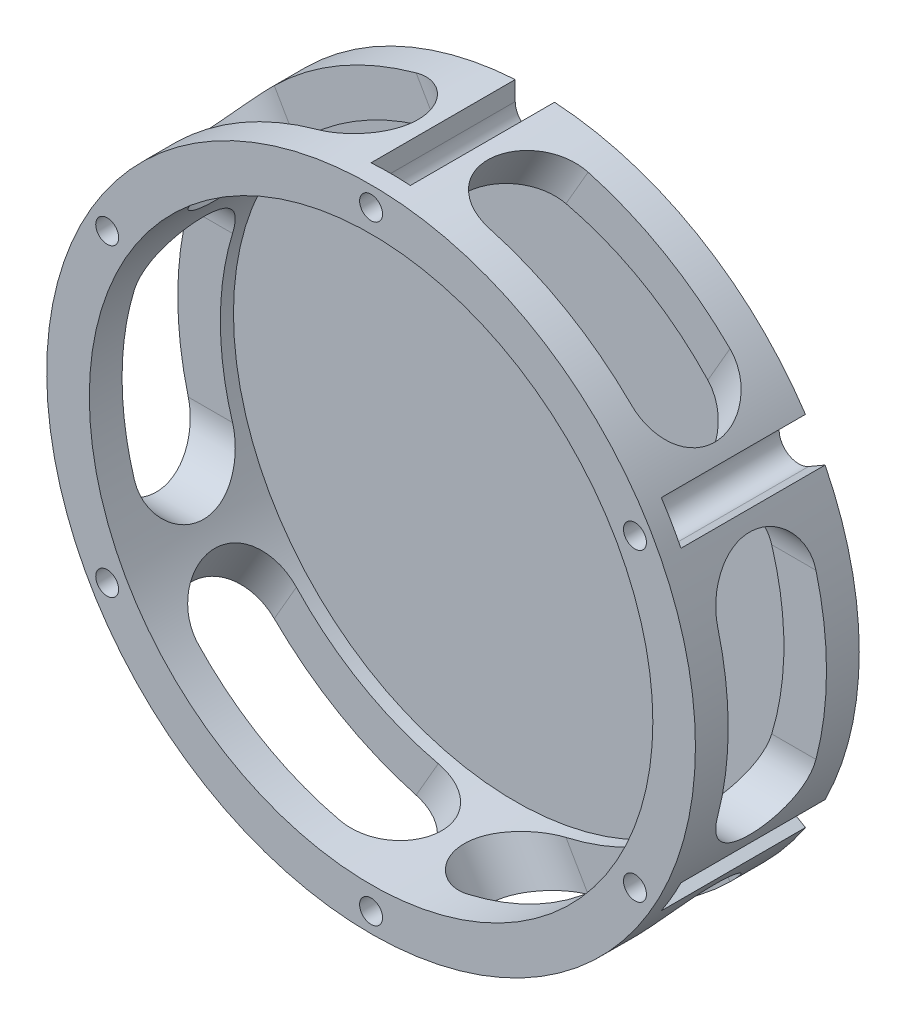
SolidWorks part; units mm, degrees
material "ABS"
ref_plane "Спереди" through (0, 0, 0) normal (0, 0, 1) x (1, 0, 0)
ref_plane "Сверху" through (0, 0, 0) normal (0, 1, 0) x (1, 0, 0)
ref_plane "Справа" through (0, 0, 0) normal (1, 0, 0) x (0, 0, -1)
sketch "Эскиз1" plane through (0, 0, 0) normal (0, 0, 1) x (1, 0, 0)
  line L0 (0, 0) -> (0, 46.5) construction
  circle A0 centre (0, 0) radius 50 construction
  circle A1 centre (0, 0) radius 43
  circle A2 centre (0, 0) radius 49.5
  circle A3 centre (0, 0) radius 46.5 construction
  circle A4 centre (0, 46.5) radius 1.75
  circle A5 centre (40.2702, 23.25) radius 1.75
  circle A6 centre (40.2702, -23.25) radius 1.75
  circle A7 centre (0, -46.5) radius 1.75
  circle A8 centre (-40.2702, -23.25) radius 1.75
  circle A9 centre (-40.2702, 23.25) radius 1.75
  point P23 (0, 0)
  dimension "D1" = 100
  dimension "D5" = 3.5
  dimension "D2" = 7
  dimension "D3" = 0.5
  dimension "D4" = 3.5
  dimension "D6" = 6
extrude "Бобышка-Вытянуть1" add sketch "Эскиз1" along normal blind 25
sketch "Эскиз2" plane through (0, 0, 0) normal (1, 0, 0) x (0, 0, -1)
  line L0 (0, 0) -> (-25, 0) construction
  line L1 (-25, 49.5) -> (-25, -49.5) construction
  line L2 (-12.5, 12.5) -> (-12.5, -12.5) construction
  line L3 (-5, 12.5) -> (-5, -12.5)
  line L4 (-20, 12.5) -> (-20, -12.5)
  arc A0 (-5, 12.5) -> (-20, 12.5) centre (-12.5, 12.5) ccw
  arc A1 (-20, -12.5) -> (-5, -12.5) centre (-12.5, -12.5) ccw
  point P7 (-12.5, 0)
  dimension "D1" = 25
  dimension "D2" = 15
extrude "Вырез-Вытянуть1" cut sketch "Эскиз2" against normal blind 59
pattern_circular "Круговой массив1" count 6 over 360 about axis through (0, 0, 25) along (0, 0, -1) of "Вырез-Вытянуть1"
sketch "Эскиз3" plane through (0, 0, 0) normal (0, 0, -1) x (-1, 0, 0)
  circle A0 centre (0, 0) radius 44.0458
extrude "Бобышка-Вытянуть2" add sketch "Эскиз3" against normal blind 3
sketch "Эскиз4" plane through (0, 0, 0) normal (0, 0, -1) x (-1, 0, 0)
  line L0 (0, 46.5) -> (0, 53.5027) construction
  line L1 (-3, 46.5) -> (-3, 53.5027)
  line L2 (3, 46.5) -> (3, 53.5027)
  line L3 (-40.2702, 23.25) -> (-46.3347, 26.7514) construction
  line L4 (-41.7702, 20.6519) -> (-47.8347, 24.1533)
  line L5 (-38.7702, 25.8481) -> (-44.8347, 29.3494)
  line L6 (-40.2702, -23.25) -> (-46.3347, -26.7514) construction
  line L7 (-38.7702, -25.8481) -> (-44.8347, -29.3494)
  line L8 (-41.7702, -20.6519) -> (-47.8347, -24.1533)
  line L9 (0, -46.5) -> (0, -53.5027) construction
  line L10 (3, -46.5) -> (3, -53.5027)
  line L11 (-3, -46.5) -> (-3, -53.5027)
  line L12 (40.2702, -23.25) -> (46.3347, -26.7514) construction
  line L13 (41.7702, -20.6519) -> (47.8347, -24.1533)
  line L14 (38.7702, -25.8481) -> (44.8347, -29.3494)
  line L15 (40.2702, 23.25) -> (46.3347, 26.7514) construction
  line L16 (38.7702, 25.8481) -> (44.8347, 29.3494)
  line L17 (41.7702, 20.6519) -> (47.8347, 24.1533)
  arc A0 (-3, 46.5) -> (3, 46.5) centre (0, 46.5) ccw
  arc A1 (3, 53.5027) -> (-3, 53.5027) centre (0, 53.5027) ccw
  arc A2 (-41.7702, 20.6519) -> (-38.7702, 25.8481) centre (-40.2702, 23.25) ccw
  arc A3 (-44.8347, 29.3494) -> (-47.8347, 24.1533) centre (-46.3347, 26.7514) ccw
  arc A4 (-38.7702, -25.8481) -> (-41.7702, -20.6519) centre (-40.2702, -23.25) ccw
  arc A5 (-47.8347, -24.1533) -> (-44.8347, -29.3494) centre (-46.3347, -26.7514) ccw
  arc A6 (3, -46.5) -> (-3, -46.5) centre (0, -46.5) ccw
  arc A7 (-3, -53.5027) -> (3, -53.5027) centre (0, -53.5027) ccw
  arc A8 (41.7702, -20.6519) -> (38.7702, -25.8481) centre (40.2702, -23.25) ccw
  arc A9 (44.8347, -29.3494) -> (47.8347, -24.1533) centre (46.3347, -26.7514) ccw
  arc A10 (38.7702, 25.8481) -> (41.7702, 20.6519) centre (40.2702, 23.25) ccw
  arc A11 (47.8347, 24.1533) -> (44.8347, 29.3494) centre (46.3347, 26.7514) ccw
  point P2 (0, 50.0014)
  point P13 (-43.3024, 25.0007)
  point P20 (-43.3024, -25.0007)
  point P27 (0, -50.0014)
  point P34 (43.3024, -25.0007)
  point P41 (43.3024, 25.0007)
  point P46 (0, 0)
  dimension "D1" = 6
  dimension "D3" = 7.0027
  dimension "D2" = 6
extrude "Вырез-Вытянуть3" cut sketch "Эскиз4" against normal blind 22
